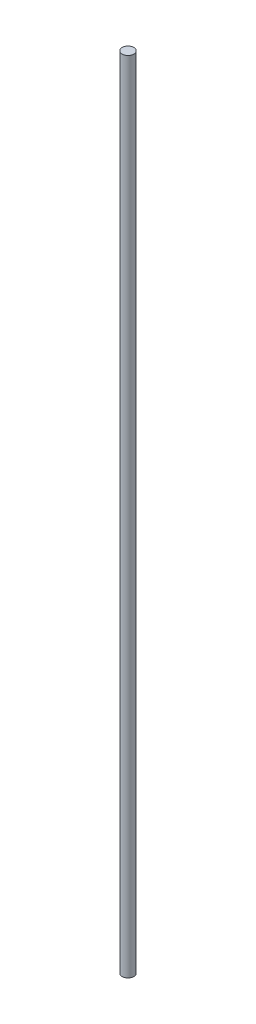
SolidWorks part; units mm, degrees
ref_plane "前视基准面" through (0, 0, 0) normal (0, 0, 1) x (1, 0, 0)
ref_plane "上视基准面" through (0, 0, 0) normal (0, 1, 0) x (1, 0, 0)
ref_plane "右视基准面" through (0, 0, 0) normal (1, 0, 0) x (0, 0, -1)
sketch "草图1" plane through (0, 0, 0) normal (0, 1, 0) x (1, 0, 0)
  circle A0 centre (0, 0) radius 4
  dimension "D1" = 8
extrude "凸台-拉伸1" add sketch "草图1" along normal blind 550
